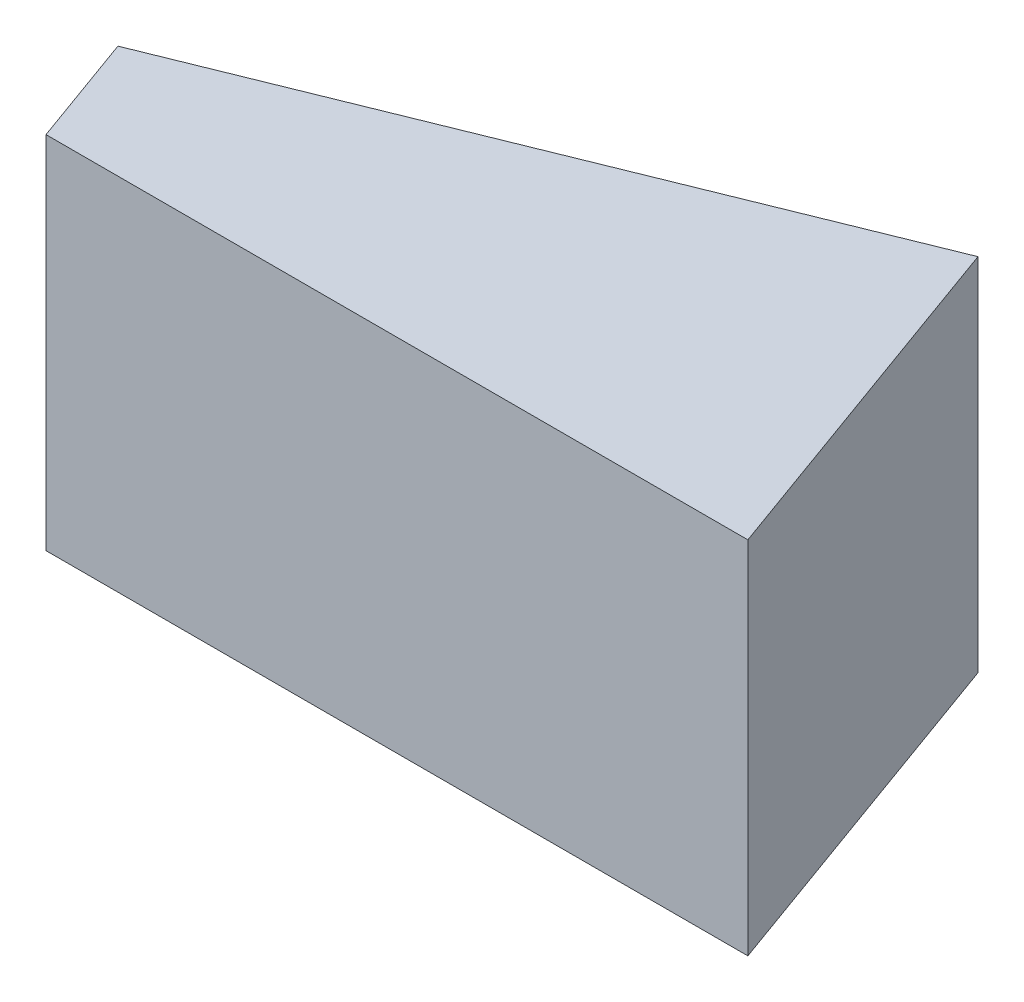
SolidWorks part; units mm, degrees
ref_plane "Front Plane" through (0, 0, 0) normal (0, 0, 1) x (1, 0, 0)
ref_plane "Top Plane" through (0, 0, 0) normal (0, 1, 0) x (1, 0, 0)
ref_plane "Right Plane" through (0, 0, 0) normal (1, 0, 0) x (0, 0, -1)
sketch "Sketch1" plane through (0, 0, 0) normal (0, 1, 0) x (1, 0, 0)
  line L0 (0, 0) -> (107.95, 0)
  line L1 (107.95, 0) -> (94.1857, 38.1)
  line L2 (94.1857, 38.1) -> (0, 0)
  line L3 (94.1857, 38.1) -> (94.1857, 0) construction
  line L4 (29.433, 11.9062) -> (33.7344, 0)
  dimension "D1" = 38.1
  dimension "D2" = 101.6
  dimension "D3" = 107.95
  dimension "D4" = 31.75
extrude "Boss-Extrude1" add sketch "Sketch1" along normal blind 38.1 contours L3 L2 L4 L0 | L1 L3 L0
